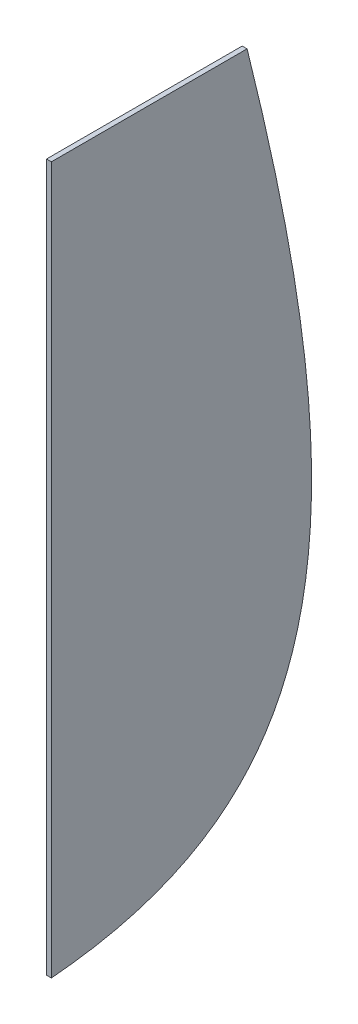
SolidWorks part; units mm, degrees
ref_plane "前视基准面" through (0, 0, 0) normal (0, 0, 1) x (1, 0, 0)
ref_plane "上视基准面" through (0, 0, 0) normal (0, 1, 0) x (1, 0, 0)
ref_plane "右视基准面" through (0, 0, 0) normal (1, 0, 0) x (0, 0, -1)
sketch "草图1" plane through (0, 0, 0) normal (0, 0, 1) x (1, 0, 0)
  line L0 (144.2985, 0) -> (0, 0) construction
  line L1 (0, 0) -> (0, -67.6179) construction
  line L2 (15, 6) -> (145, 6) construction
  line L3 (145, 6) -> (145, 0) construction
  line L4 (15, 6) -> (15, 0) construction
  line L5 (0, 0) -> (0, -71.7115) construction
  line L10 (0, 0) -> (145, -37) construction
  line L11 (145, -4) -> (18, -39.7537) construction
  line L12 (0, 0) -> (33.0829, -39.4266) construction
  line L13 (0, -40.144) -> (145, -37) construction
  line L14 (145, -37) -> (145, 0) construction
  line L17 (15, 0) -> (145, 0)
  line L21 (0, -40.144) -> (96.1056, -64.0701) construction
  line L22 (96.1056, -64.0701) -> (140.0538, -58.2825) construction
  line L23 (140.0538, -58.2825) -> (145, 0) construction
  line L24 (0, -40.144) -> (0, 0)
  line L25 (0, 0) -> (15, 0)
  spline S0 degree 3 poles (0, -40.144) (96.1056, -64.0701) (140.0538, -58.2825) (145, 0) knots 0 0 0 0 1 1 1 1
  dimension "D5" = 0
  dimension "D1" = 6
  dimension "D2" = 145
  dimension "D8" = 40
  dimension "D9" = 18
  dimension "D10" = 4
  dimension "D11" = 37
extrude "凸台-拉伸1" add sketch "草图1" along normal mid plane 1
fillet "圆角1" [suppressed] radius 5
move or copy body "实体-移动/复制1" bodies to move or copy 101 copy no rotation origin (0, 0, 0) rotation axis (0, 1, 0) rotation angle 180
move or copy body "实体-移动/复制2" bodies to move or copy 103 copy no rotation origin (0, 0, 0) rotation axis (0, 0, -1) rotation angle 90
move or copy body "实体-移动/复制3" bodies to move or copy 104 copy no rotation origin (0, 0, 0) rotation axis (0, -1, 0) rotation angle 90
move or copy body "实体-移动/复制4" bodies to move or copy 105 copy no rotation origin (0, 0, 0) rotation axis (0, 0, 1) rotation angle 180
